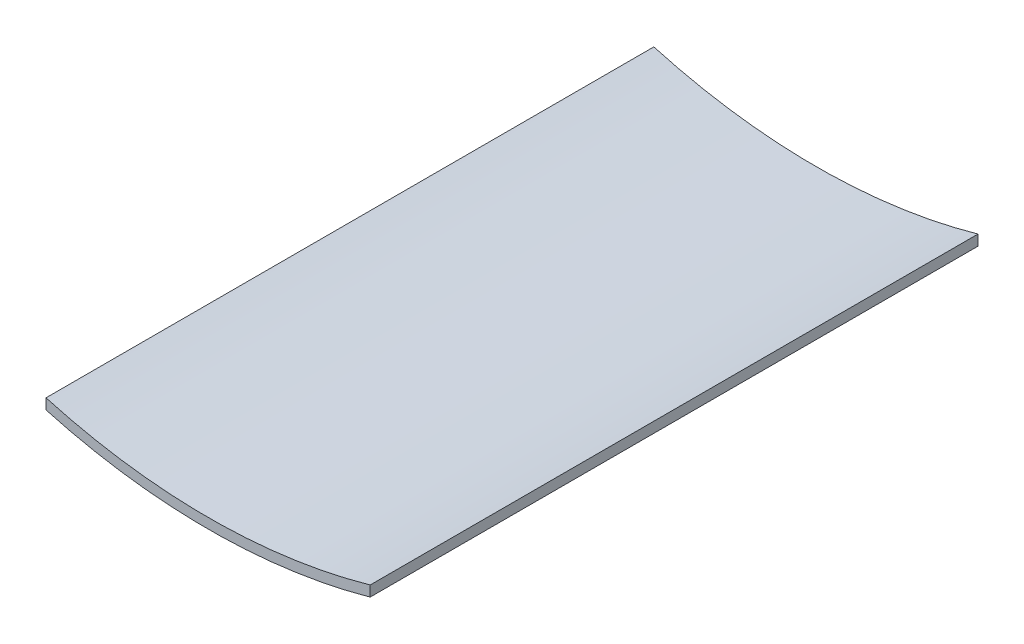
SolidWorks part; units mm, degrees
ref_plane "Front Plane" through (0, 0, 0) normal (1, 0, 0) x (0, 1, 0)
ref_plane "Top Plane" through (0, 0, 0) normal (0, 0, 1) x (0, 1, 0)
ref_plane "Right Plane" through (0, 0, 0) normal (0, 1, 0) x (-1, 0, 0)
sketch "Sketch1" plane through (0, 0, 0) normal (0, 0, 1) x (0, 1, 0)
  line L0 (0, -50.8) -> (-182.2837, -50.8) construction
  line L1 (0, 0) -> (0, 50.8) construction
  line L2 (0, 0) -> (-182.2837, 0) construction
  line L3 (0, 50.8) -> (-182.2837, 50.8) construction
  line L4 (-182.2837, 0) -> (-182.2837, 50.8) construction
  line L5 (-182.2837, 50.8) -> (-178.9855, 50.8)
  line L6 (-182.2837, -50.8) -> (-178.9855, -50.8)
  circle A0 centre (0, 0) radius 50.8 construction
  circle A1 centre (0, 0) radius 186.055 construction
  circle A2 centre (0, 0) radius 189.23 construction
  arc A3 (-178.9855, 50.8) -> (-178.9855, -50.8) centre (0, 0) ccw
  arc A4 (-182.2837, 50.8) -> (-182.2837, -50.8) centre (0, 0) ccw
  dimension "D1" = 101.6
  dimension "D2" = 135.255
  dimension "D3" = 3.175
  dimension "D4" = 0
extrude "Boss-Extrude1" add sketch "Sketch1" along normal blind 190.5
